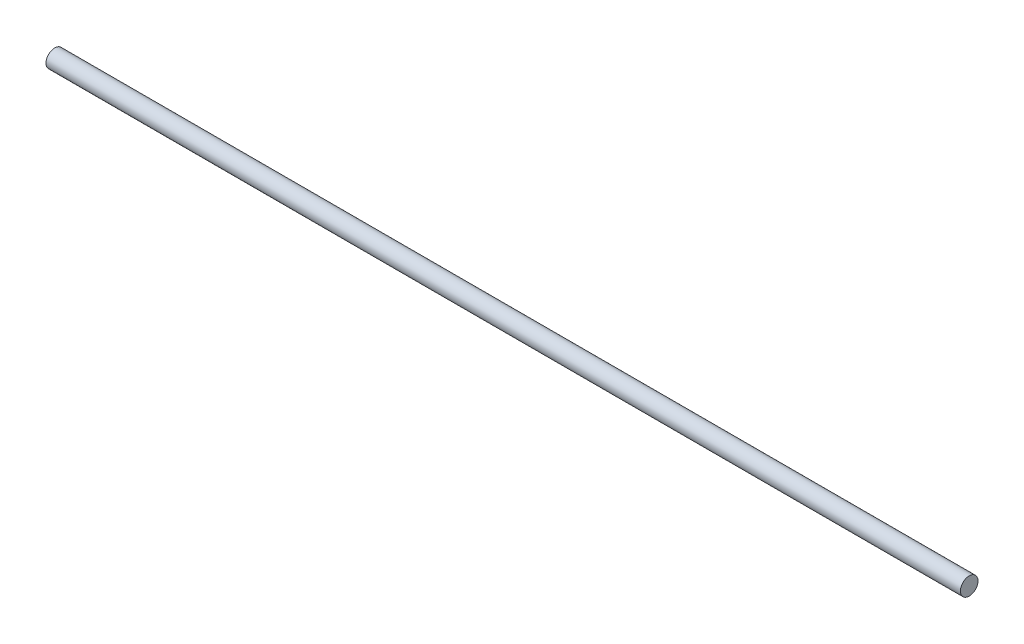
SolidWorks part; units mm, degrees
ref_plane "Front Plane" through (0, 0, 0) normal (0, 0, 1) x (1, 0, 0)
ref_plane "Top Plane" through (0, 0, 0) normal (0, 1, 0) x (1, 0, 0)
ref_plane "Right Plane" through (0, 0, 0) normal (1, 0, 0) x (0, 0, -1)
sketch "Sketch1" plane through (0, 0, 0) normal (1, 0, 0) x (0, 0, -1)
  circle A0 centre (0, 0) radius 5
  dimension "D1" = 10
extrude "Boss-Extrude1" add sketch "Sketch1" against normal blind 520
